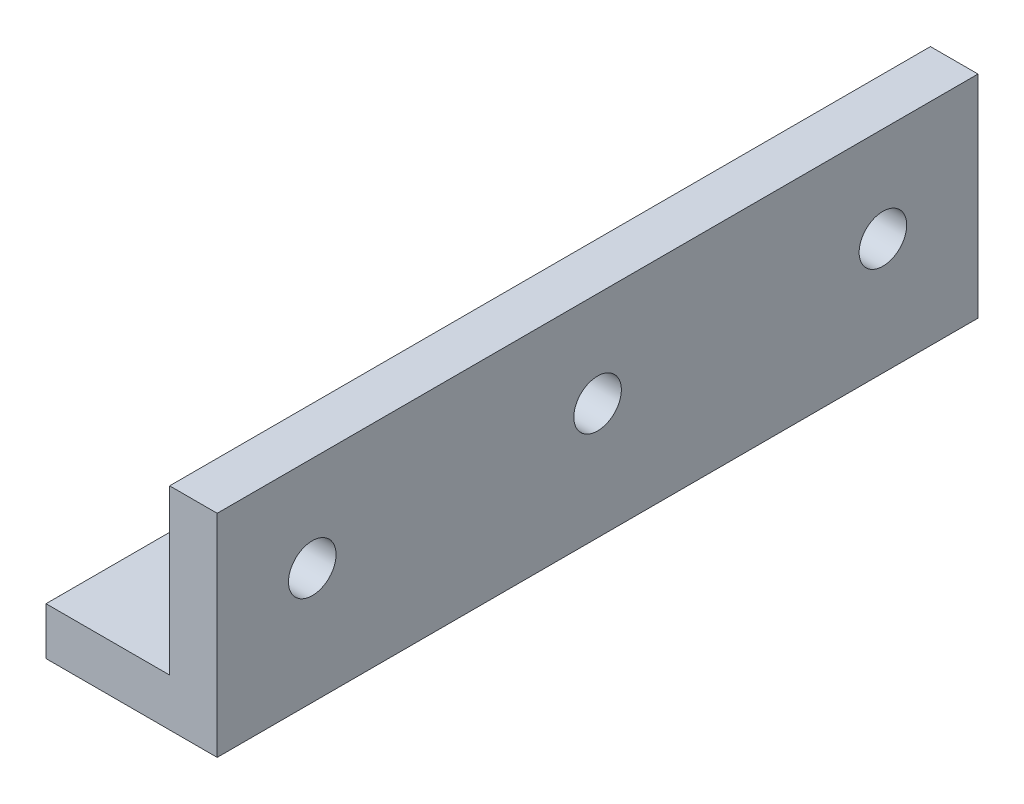
SolidWorks part; units mm, degrees
ref_plane "Front Plane" through (0, 0, 0) normal (0, 0, 1) x (1, 0, 0)
ref_plane "Top Plane" through (0, 0, 0) normal (0, 1, 0) x (1, 0, 0)
ref_plane "Right Plane" through (0, 0, 0) normal (1, 0, 0) x (0, 0, -1)
sketch "Sketch1" plane through (0, 0, 0) normal (0, 1, 0) x (1, 0, 0)
  line L0 (0, 0) -> (22.86, 0)
  line L1 (22.86, 0) -> (22.86, -101.6)
  line L2 (22.86, -101.6) -> (0, -101.6)
  line L3 (0, -101.6) -> (0, 0)
  dimension "D1" = 22.86
  dimension "D2" = 22.86
  dimension "D3" = 101.6
extrude "Boss-Extrude1" add sketch "Sketch1" along normal blind 6.35
sketch "Sketch4" plane through (0, 6.35, 0) normal (0, 1, 0) x (1, 0, 0)
  line L0 (22.86, 0) -> (0, 0) construction
  line L1 (22.86, -101.6) -> (16.51, -101.6)
  line L2 (22.86, -101.6) -> (22.86, 0)
  line L3 (22.86, 0) -> (16.51, 0)
  line L4 (16.51, -101.6) -> (16.51, 0)
  dimension "D1" = 6.35
extrude "Boss-Extrude2" add sketch "Sketch4" along normal blind 21.8854
sketch "Sketch7" plane through (16.51, 0, 0) normal (-1, 0, 0) x (0, 0, 1)
  line L1 (0, 28.2354) -> (0, 6.35) construction
  line L2 (0, 28.2354) -> (101.6, 28.2354) construction
  circle A0 centre (88.9, 15.5354) radius 3.175
  circle A1 centre (50.8, 15.5354) radius 3.175
  circle A2 centre (12.7, 15.5354) radius 3.175
  dimension "D1" = 6.35
  dimension "D2" = 6.35
  dimension "D3" = 6.35
  dimension "D4" = 38.1
  dimension "D5" = 76.2
  dimension "D6" = 12.7
  dimension "D7" = 12.7
  dimension "D8" = 12.7
  dimension "D9" = 12.7
extrude "Cut-Extrude1" cut sketch "Sketch7" against normal up to surface (6.35 mm away) up to face at (22.86, 14.1177, 50.8)
sketch "Sketch8" plane through (0, 6.35, 0) normal (0, 1, 0) x (1, 0, 0)
  line L0 (16.51, 0) -> (0, 0) construction
  line L1 (16.51, 0) -> (16.51, -101.6) construction
  circle A0 centre (10.16, -31.75) radius 3.175
  circle A2 centre (10.16, -69.85) radius 3.175
  dimension "D1" = 6.35
  dimension "D2" = 38.1
  dimension "D3" = 6.35
  dimension "D6" = 31.75
  dimension "D7" = 6.35
  dimension "D9" = 6.35
extrude "Cut-Extrude2" cut sketch "Sketch8" against normal up to surface (6.35 mm away) up to face at (11.43, 0, 50.8)
